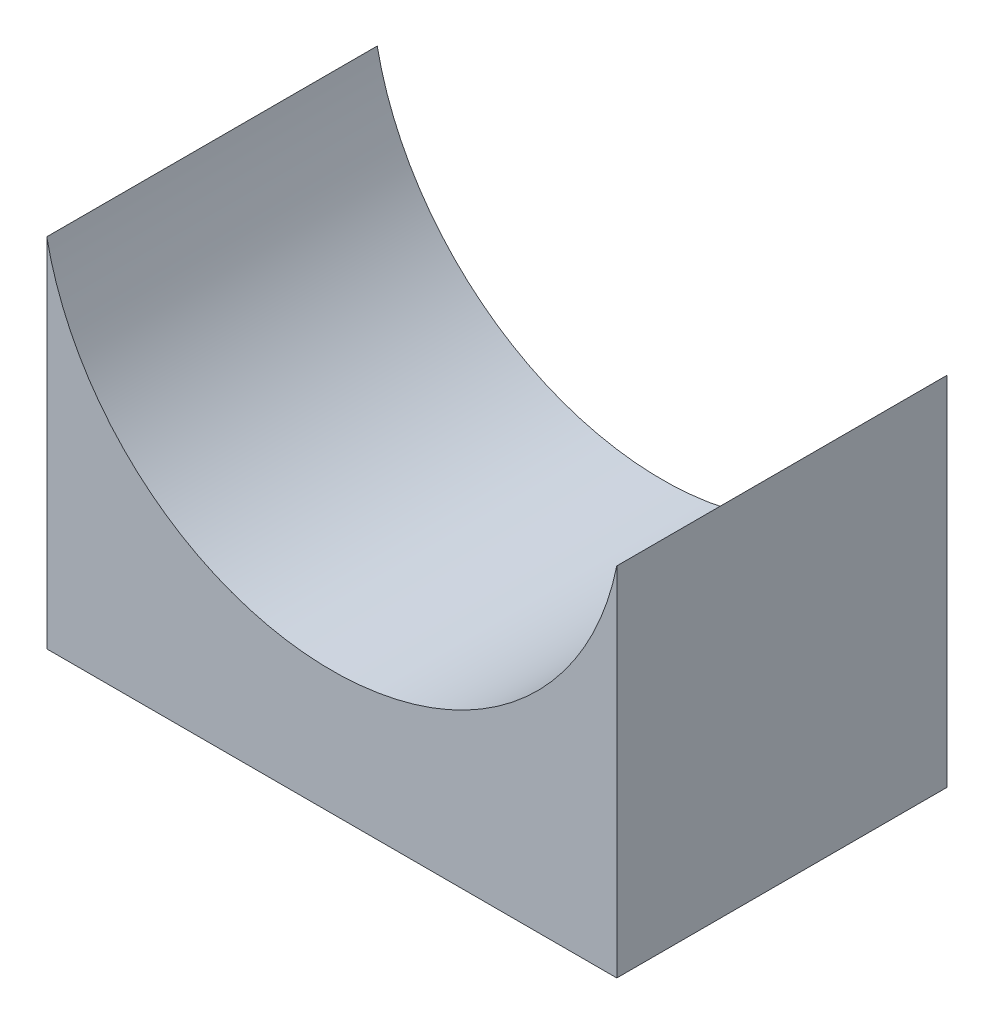
SolidWorks part; units mm, degrees
ref_plane "Front Plane" through (0, 0, 0) normal (0, 0, 1) x (1, 0, 0)
ref_plane "Top Plane" through (0, 0, 0) normal (0, 1, 0) x (1, 0, 0)
ref_plane "Right Plane" through (0, 0, 0) normal (1, 0, 0) x (0, 0, -1)
sketch "Sketch1" plane through (0, 0, 0) normal (0, 0, 1) x (1, 0, 0)
  line L0 (-21.9075, -31.8675) -> (21.9075, -31.8675)
  line L1 (-21.9075, -4.4355) -> (-21.9075, -31.8675)
  line L2 (21.9075, -4.4355) -> (21.9075, -31.8675)
  arc A0 (-21.9075, -4.4355) -> (21.9075, -4.4355) centre (0, 0) ccw
  point P4 (0, 0)
  point P7 (0, 0)
  point P8 (0, 0)
  point P9 (0, 3.175)
  point P10 (0, 25.527)
  point P11 (-21.9075, 21.0915)
  point P12 (0, -22.352)
  point P13 (0, 0)
  dimension "D1" = 44.704
  dimension "D3" = 27.432
  dimension "D2" = 43.815
extrude "Boss-Extrude1" add sketch "Sketch1" along normal blind 25.4
